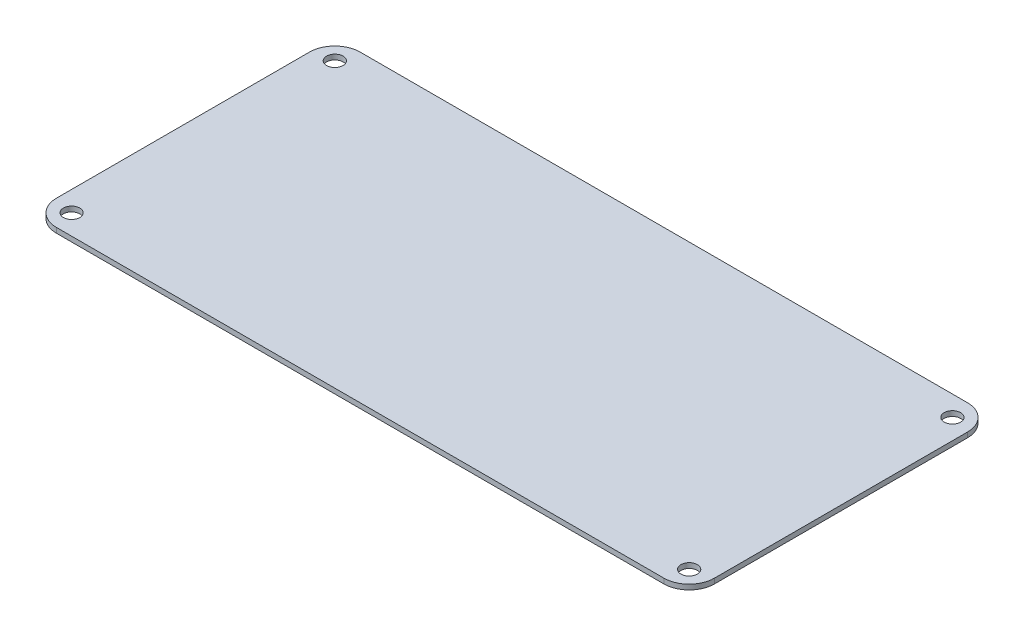
SolidWorks part; units mm, degrees
ref_plane "前视基准面" through (0, 0, 0) normal (0, 0, 1) x (1, 0, 0)
ref_plane "上视基准面" through (0, 0, 0) normal (0, 1, 0) x (1, 0, 0)
ref_plane "右视基准面" through (0, 0, 0) normal (1, 0, 0) x (0, 0, -1)
sketch "草图1" plane through (0, 0, 0) normal (0, 1, 0) x (1, 0, 0)
  line L0 (-130, 50) -> (-130, -50)
  line L1 (-120, -60) -> (120, -60)
  line L2 (130, -50) -> (130, 50)
  line L3 (120, 60) -> (-120, 60)
  arc A0 (-130, -50) -> (-120, -60) centre (-120, -50) ccw
  arc A1 (120, -60) -> (130, -50) centre (120, -50) ccw
  arc A2 (130, 50) -> (120, 60) centre (120, 50) ccw
  arc A3 (-120, 60) -> (-130, 50) centre (-120, 50) ccw
extrude "凸台-拉伸1" add sketch "草图1" along normal blind 2
sketch "草图3" plane through (0, 2, 0) normal (0, 1, 0) x (1, 0, 0)
  line L0 (-130, 50) -> (-130, -50)
  line L1 (-120, -60) -> (120, -60)
  line L2 (130, -50) -> (130, 50)
  line L3 (120, 60) -> (-120, 60)
  line L5 (-122, 52) -> (122, 52) construction
  line L6 (-122, 52) -> (-122, -52) construction
  line L7 (-122, -52) -> (122, -52) construction
  line L8 (122, 52) -> (122, -52) construction
  circle A0 centre (-122, 52) radius 3.25
  circle A1 centre (-122, -52) radius 3.25
  arc A2 (-130, -50) -> (-120, -60) centre (-120, -50) ccw
  arc A3 (120, -60) -> (130, -50) centre (120, -50) ccw
  arc A4 (130, 50) -> (120, 60) centre (120, 50) ccw
  arc A5 (-120, 60) -> (-130, 50) centre (-120, 50) ccw
  circle A6 centre (122, -52) radius 3.25
  circle A7 centre (122, 52) radius 3.25
  dimension "D1" = 6.5
  dimension "D2" = 6.5
  dimension "D3" = 6.5
  dimension "D4" = 6.5
extrude "切除-拉伸2" cut sketch "草图3" against normal blind 15 contours A0 | A1 | A6 | A7
